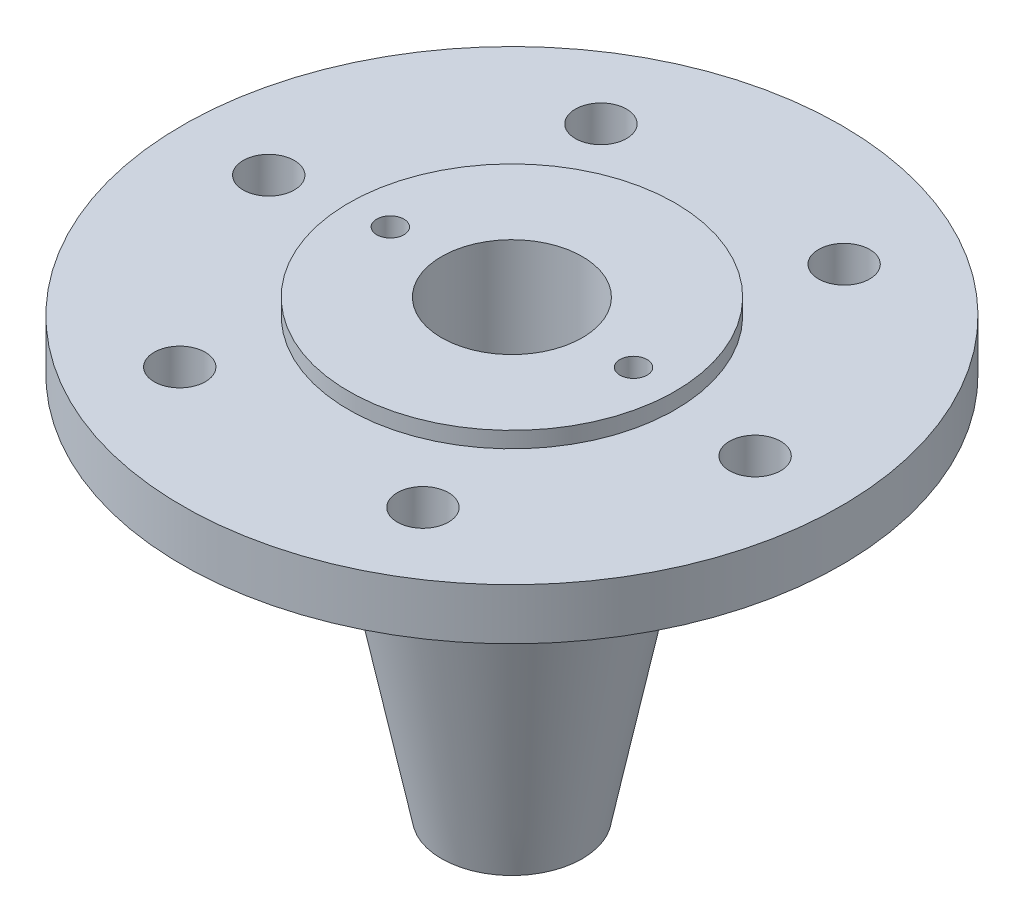
SolidWorks part; units mm, degrees
ref_plane "Piano frontale" through (0, 0, 0) normal (0, 0, 1) x (1, 0, 0)
ref_plane "Piano superiore" through (0, 0, 0) normal (0, 1, 0) x (1, 0, 0)
ref_plane "Piano destro" through (0, 0, 0) normal (1, 0, 0) x (0, 0, -1)
sketch "Schizzo1" plane through (0, 0, 0) normal (0, 0, 1) x (1, 0, 0)
  line L0 (0, 0) -> (51, 0)
  line L1 (51, 0) -> (51, -5)
  line L2 (51, -5) -> (103, -5)
  line L3 (103, -5) -> (103, -21)
  line L4 (103, -21) -> (54, -21)
  line L5 (54, -21) -> (54, -31)
  line L6 (54, -31) -> (44, -31)
  line L7 (44, -31) -> (22, -141)
  line L8 (22, -141) -> (0, -141)
  line L9 (0, -141) -> (0, 0) construction
  line L10 (0, 0) -> (0, -141)
  dimension "D1" = 206
  dimension "D2" = 44
  dimension "D3" = 108
  dimension "D4" = 102
  dimension "D5" = 88
  dimension "D6" = 5
  dimension "D7" = 16
  dimension "D8" = 10
  dimension "D9" = 120
revolve "Rivoluzione1" add sketch "Schizzo1" angle 360 about L9
sketch "Schizzo2" plane through (0, 0, 0) normal (0, 0, 1) x (1, 0, 0)
  line L0 (0, 0) -> (0, -141) construction
  line L1 (51, 0) -> (-51, 0) construction
  line L2 (-22, -141) -> (22, -141) construction
  line L3 (0, -141) -> (-11.75, -141)
  line L4 (-11.75, -141) -> (-11.75, -103)
  line L5 (-11.75, -103) -> (-16, -100.24)
  line L6 (-16, -100.24) -> (-16, -86.247)
  line L7 (-16, -86.247) -> (-11, -83)
  line L8 (-11, -83) -> (-11, -51.1435)
  line L9 (-11, -51.1435) -> (-22, -44)
  line L10 (-22, -44) -> (-22, 0)
  line L11 (-22, 0) -> (0, 0)
  line L12 (0, 0) -> (0, -141)
  point P12 (-16, -103)
  point P15 (-16, -93.0856)
  point P16 (-16, -99.0516)
  dimension "D1" = 44
  dimension "D2" = 44
  dimension "D3" = 32
  dimension "D4" = 22
  dimension "D5" = 23.5
  dimension "D6" = 38
  dimension "D7" = 33
  dimension "D8" = 33
  dimension "D9" = 33
  dimension "D10" = 20
revolve "Taglia-Rivoluzione1" cut sketch "Schizzo2" angle 360 about L0
cosmetic thread "Filettatura cosmetica1" parameters "D2"=25
fillet "Raccordo1" radius 5 1 edges at (0, -31, -44)
hole_wizard "Foro Ø1.0 (16)-1" positions "Schizzo4" profile "Schizzo5" hole size "Ø1.0" standard "Ansi Metric" end condition up to next
sketch "Schizzo4" plane through (0, -5, 0) normal (0, 1, 0) x (1, 0, 0)
  circle A0 centre (0, 0) radius 76
  point P5 (-76, 0)
  dimension "D1" = 152
sketch "Schizzo5" plane through (-76, -5, 0) normal (1, 0, 0) x (0, 0, 1)
  line L0 (0, 0) -> (0, 16)
  line L1 (0, 16) -> (8, 16)
  line L2 (8, 16) -> (8, 0)
  line L5 (8, 0) -> (0, 0)
  line L11 (0, -6.35) -> (0, 107.95) construction
  dimension "Thru Hole Dia." = 16
  dimension "Thru Hole Depth" = 16
pattern_circular "RipetizioneCircolare1" count 6 over 360 about axis through (0, 0, 0) along (0, 1, 0) of "Foro Ø1.0 (16)-1"
hole_wizard "Foro filettato M10x1.5-1" positions "Schizzo6" profile "Schizzo7" tap size "M10x1.5" standard "Ansi Metric"
sketch "Schizzo6" plane through (0, 0, 0) normal (0, 1, 0) x (1, 0, 0)
  circle A0 centre (0, 0) radius 38 construction
  point P5 (-38, 0)
  point P7 (38, 0)
  dimension "D1" = 76
sketch "Schizzo7" plane through (38, 0, 0) normal (1, 0, 0) x (0, 0, 1)
  line L0 (0, 0) -> (0, 20.5537)
  line L1 (0, 20.5537) -> (4.25, 18)
  line L2 (4.25, 18) -> (4.25, 0)
  line L5 (4.25, 0) -> (0, 0)
  line L10 (0, 20.5537) -> (-4.25, 18) construction
  line L11 (0, -6.35) -> (0, 107.95) construction
  dimension "Tap Drill Dia." = 8.5
  dimension "Tap Drill Depth" = 18
  dimension "Drill Angle" = 118
cosmetic thread "Filettatura del foro1" parameters "D1"=15, "D2"=10
cosmetic thread "Filettatura del foro2" parameters "D1"=15, "D2"=10
